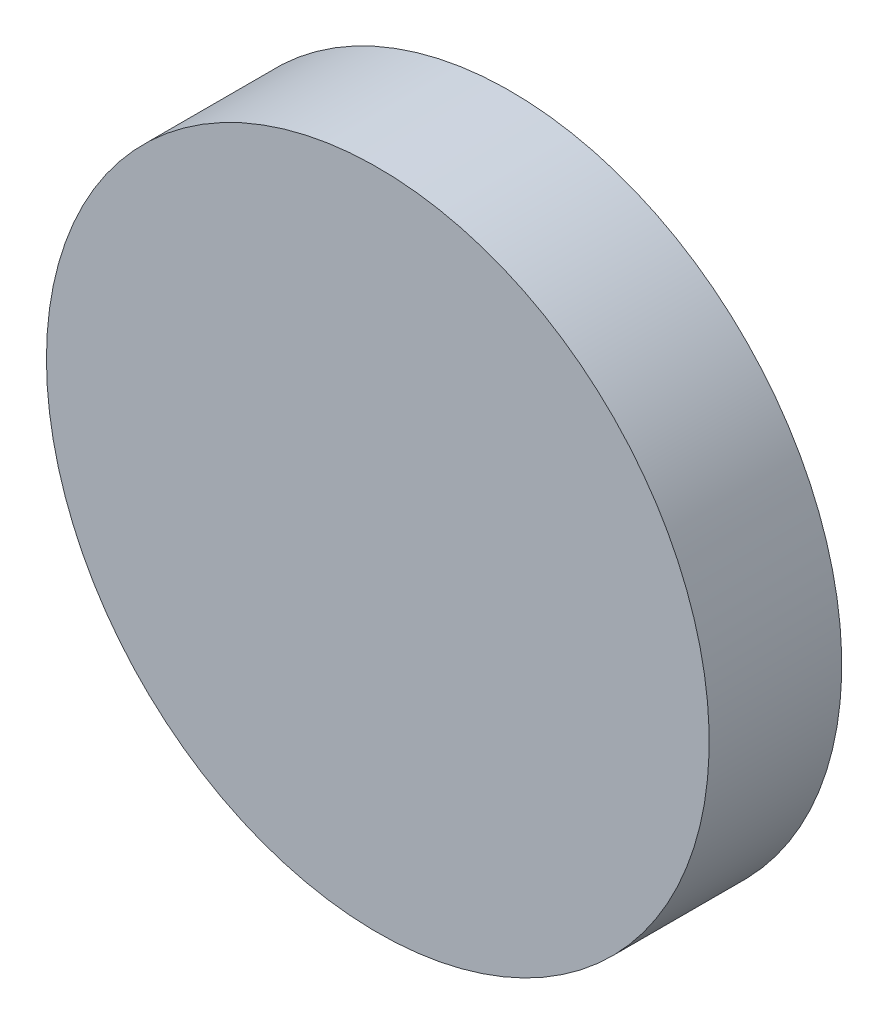
SolidWorks part; units mm, degrees
ref_plane "Přední rovina" through (0, 0, 0) normal (0, 0, 1) x (1, 0, 0)
ref_plane "Horní rovina" through (0, 0, 0) normal (0, 1, 0) x (1, 0, 0)
ref_plane "Pravá rovina" through (0, 0, 0) normal (1, 0, 0) x (0, 0, -1)
sketch "Sketch1" plane through (0, 0, 0) normal (0, 1, 0) x (1, 0, 0)
  line L1 (-50, 0) -> (-40, 0)
  line L2 (-50, 0) -> (-50, -20)
  line L3 (-50, -20) -> (0, -20)
  line L6 (-40, 0) -> (-40, -10)
  line L7 (-40, -10) -> (0, -10)
  line L9 (0, 0) -> (0, -20) construction
  line L13 (0, -20) -> (0, -10)
  point P3 (0, -10)
  dimension "D1" = 50
  dimension "D2" = 10
  dimension "D3" = 10
  dimension "D4" = 10
revolve "Revolve1" add sketch "Sketch1" angle 360 about L9
